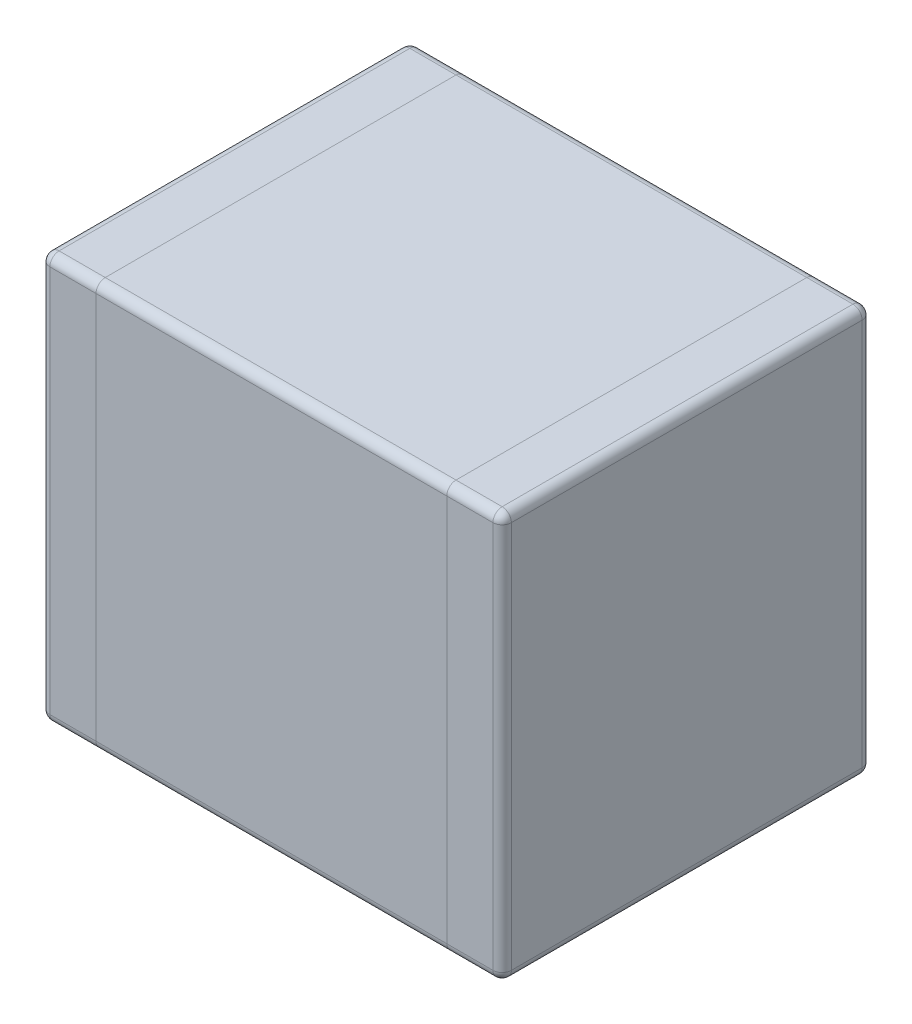
SolidWorks part; units mm, degrees
ref_plane "Front Plane" through (0, 0, 0) normal (0, 0, 1) x (1, 0, 0)
ref_plane "Top Plane" through (0, 0, 0) normal (0, 1, 0) x (1, 0, 0)
ref_plane "Right Plane" through (0, 0, 0) normal (1, 0, 0) x (0, 0, -1)
sketch "Sketch1" plane through (0, 0, 0) normal (0, 1, 0) x (1, 0, 0)
  line L1 (-1.25, -1) -> (1.25, -1)
  line L2 (-1.25, -1) -> (-1.25, 1)
  line L3 (-1.25, 1) -> (1.25, 1)
  line L4 (1.25, -1) -> (1.25, 1)
  line L5 (-1.25, -1) -> (1.25, 1) construction
  line L6 (-1.25, 1) -> (1.25, -1) construction
  point P0 (0, 0)
  dimension "D1" = 2.5
  dimension "D2" = 2
extrude "Extrude1" add sketch "Sketch1" along normal blind 2.2
fillet "Fillet1" radius 0.05 12 edges at (1.25, 1.1, -1) (-1.25, 1.1, -1) (-1.25, 1.1, 1) (1.25, 1.1, 1) (0, 2.2, 1) (-1.25, 2.2, 0) (0, 2.2, -1) (1.25, 2.2, 0) (0, 0, -1) (-1.25, 0, 0) (0, 0, 1) (1.25, 0, 0)
sketch "Sketch2" plane through (0, 0, 0) normal (0, 1, 0) x (1, 0, 0)
  line L0 (-1.2, 1) -> (1.2, 1) construction
  line L1 (-0.95, -1) -> (0.95, -1)
  line L2 (-0.95, -1) -> (-0.95, 1)
  line L3 (-0.95, 1) -> (0.95, 1)
  line L4 (0.95, -1) -> (0.95, 1)
  line L5 (1.2, -1) -> (-1.2, -1) construction
  line L6 (0, 0.95) -> (0, -0.6635) construction
  line L7 (1.2, 0.95) -> (-1.2, 0.95) construction
  line L9 (-1.25, -0.95) -> (-1.25, 0.95) construction
  dimension "D1" = 0.3
split line "Split Line3"
